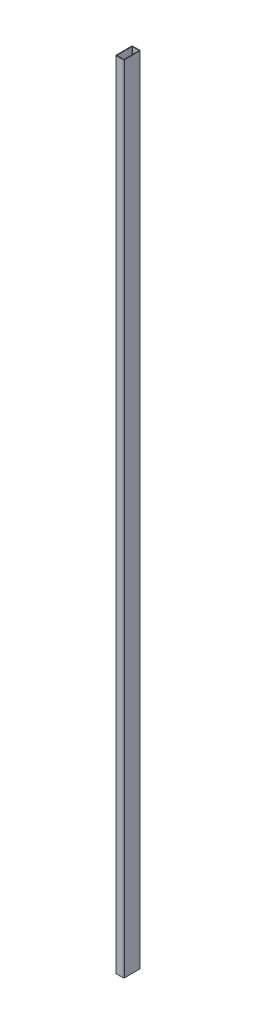
SolidWorks part; units mm, degrees
material "СТ3КП"
ref_plane "Спереди" through (0, 0, 0) normal (0, 0, 1) x (1, 0, 0)
ref_plane "Сверху" through (0, 0, 0) normal (0, 1, 0) x (1, 0, 0)
ref_plane "Справа" through (0, 0, 0) normal (1, 0, 0) x (0, 0, -1)
sketch "Эскиз1" plane through (0, 0, 0) normal (0, 1, 0) x (1, 0, 0)
  line L0 (0, -1000) -> (0, 1000) construction
  point P0 (0, 0)
  line B0 (0, 18.5) -> (0, -18.5)
  line B1 (1.5, 20) -> (18.5, 20)
  line B2 (20, 18.5) -> (20, -18.5)
  line B3 (1.5, -20) -> (18.5, -20)
  line B4 (1.5, 17.5) -> (1.5, -17.5)
  line B5 (2.5, 18.5) -> (17.5, 18.5)
  line B6 (18.5, 17.5) -> (18.5, -17.5)
  line B7 (2.5, -18.5) -> (17.5, -18.5)
  arc B8 (18.5, 20) -> (20, 18.5) centre (18.5, 18.5) cw
  arc B9 (20, -18.5) -> (18.5, -20) centre (18.5, -18.5) cw
  arc B10 (0, -18.5) -> (1.5, -20) centre (1.5, -18.5) ccw
  arc B11 (0, 18.5) -> (1.5, 20) centre (1.5, 18.5) cw
  arc B12 (18.5, -17.5) -> (17.5, -18.5) centre (17.5, -17.5) cw
  arc B13 (17.5, 18.5) -> (18.5, 17.5) centre (17.5, 17.5) cw
  arc B14 (1.5, 17.5) -> (2.5, 18.5) centre (2.5, 17.5) cw
  arc B15 (1.5, -17.5) -> (2.5, -18.5) centre (2.5, -17.5) ccw
sketch_block_instance "40х20х1_5-1"
sketch_block "40х20х1_5" parameters "D5"=1.5, "D6"=1, "D1"=1.5, "D2"=1.5, "D3"=40, "D4"=20, "D7"=14, "D8"=33
extrude "Бобышка-Вытянуть1" add sketch "Эскиз1" along normal up to surface (1920 mm away)
equation "\"D2@40х20х1_5\"=\"D1@40х20х1_5\""
equation "\"D7@40х20х1_5\"=\"D1@40х20х1_5\""
equation "\"D8@40х20х1_5\"=\"D1@40х20х1_5\""
equation "\"D5@40х20х1_5\"=\"D1@40х20х1_5\""
equation "\"D6@40х20х1_5\"=\"D5@40х20х1_5\"-0.5"
